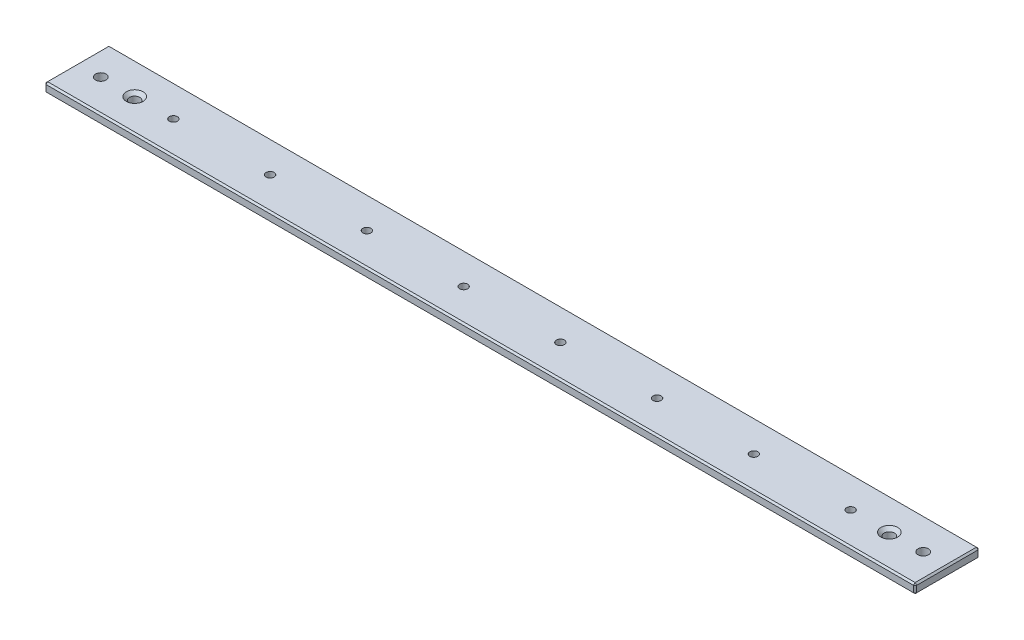
SolidWorks part; units mm, degrees
ref_plane "Front Plane" through (0, 0, 0) normal (0, 0, 1) x (1, 0, 0)
ref_plane "Top Plane" through (0, 0, 0) normal (0, 1, 0) x (1, 0, 0)
ref_plane "Right Plane" through (0, 0, 0) normal (1, 0, 0) x (0, 0, -1)
sketch "Sketch1" plane through (0, 0, 0) normal (0, 1, 0) x (1, 0, 0)
  line L1 (-135, 10) -> (135, 10)
  line L2 (-135, 10) -> (-135, -10)
  line L3 (-135, -10) -> (135, -10)
  line L4 (135, 10) -> (135, -10)
  line L5 (-135, 10) -> (135, -10) construction
  line L6 (-135, -10) -> (135, 10) construction
  point P0 (0, 0)
  dimension "D1" = 270
  dimension "D2" = 20
extrude "Boss-Extrude1" add sketch "Sketch1" along normal blind 3
sketch "Sketch2" plane through (0, 3, 0) normal (0, 1, 0) x (1, 0, 0)
  line L0 (-135, 10) -> (-135, -10) construction
  line L1 (135, -10) -> (135, 10) construction
  point P2 (-105, 0)
  point P3 (-75, 0)
  point P4 (-45, 0)
  point P5 (-15, 0)
  point P6 (15, 0)
  point P7 (45, 0)
  point P8 (75, 0)
  point P9 (105, 0)
  dimension "D1" = 30
  dimension "D2" = 30
  dimension "D3" = 30
  dimension "D4" = 30
  dimension "D5" = 30
  dimension "D6" = 30
  dimension "D7" = 30
  dimension "D8" = 30
hole_wizard "M3 Tapped Hole1" positions "3DSketch1" profile "Sketch3" tap size "M3" standard "ISO" end condition through all
sketch3d "3DSketch1"
  point P0 (-105, 3, 0)
  point P3 (-75, 3, 0)
  point P6 (-45, 3, 0)
  point P9 (-15, 3, 0)
  point P12 (15, 3, 0)
  point P15 (45, 3, 0)
  point P18 (75, 3, 0)
  point P21 (105, 3, 0)
sketch "Sketch3" plane through (-105, 3, 0) normal (1, 0, 0) x (0, 0, 1)
  line L0 (0, 0) -> (0, 3)
  line L1 (0, 3) -> (1.25, 3)
  line L2 (1.25, 3) -> (1.25, 0)
  line L5 (1.25, 0) -> (0, 0)
  line L11 (0, -6.35) -> (0, 107.95) construction
  dimension "Thru Tap Drill Dia." = 2.5
  dimension "Thru Tap Drill Depth" = 3
cosmetic thread "Hole Thread1" parameters "D2"=3
cosmetic thread "Hole Thread2" parameters "D2"=3
cosmetic thread "Hole Thread3" parameters "D2"=3
cosmetic thread "Hole Thread4" parameters "D2"=3
cosmetic thread "Hole Thread5" parameters "D2"=3
cosmetic thread "Hole Thread6" parameters "D2"=3
cosmetic thread "Hole Thread7" parameters "D2"=3
cosmetic thread "Hole Thread8" parameters "D2"=3
sketch "Sketch4" plane through (0, 3, 0) normal (0, 1, 0) x (1, 0, 0)
  line L0 (-135, 10) -> (-135, -10) construction
  line L1 (135, -10) -> (135, 10) construction
  circle A0 centre (-127.5, 0) radius 1.625
  circle A1 centre (127.5, 0) radius 1.625
  dimension "D1" = 3.25
  dimension "D2" = 3.25
  dimension "D4" = 7.5
  dimension "D3" = 7.5
extrude "Cut-Extrude1" cut sketch "Sketch4" against normal through all
chamfer "Chamfer1" distance 0.5 angle 45 12 edges at (135, 1.5, -10) (135, 1.5, 10) (-135, 1.5, -10) (-135, 0, 0) (0, 0, -10) (135, 0, 0) (0, 0, 10) (-135, 1.5, 10) (135, 3, 0) (0, 3, 10) (-135, 3, 0) (0, 3, -10)
sketch "Sketch5" plane through (0, 3, 0) normal (0, 1, 0) x (1, 0, 0)
  line L0 (-135, -9.5) -> (-135, 9.5) construction
  line L1 (135, 9.5) -> (135, -9.5) construction
  circle A0 centre (-117, 0) radius 1.6
  circle A1 centre (117, 0) radius 1.6
  dimension "D2" = 3.2
  dimension "D3" = 18
  dimension "D4" = 3.2
  dimension "D1" = 18
extrude "Cut-Extrude2" cut sketch "Sketch5" against normal through all
chamfer "Chamfer2" distance 1 angle 45 2 edges at (117, 3, 1.6) (-117, 3, 1.6)
